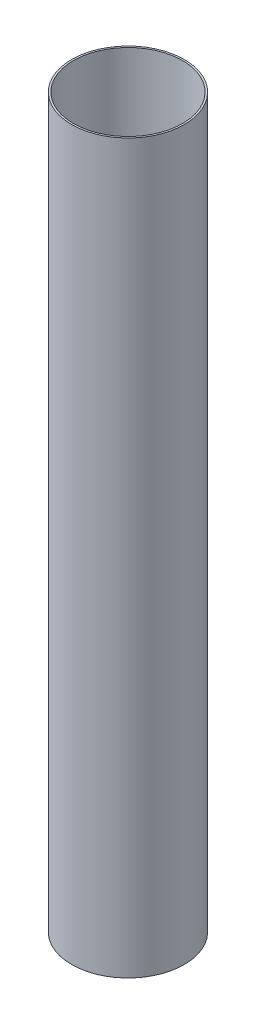
SolidWorks part; units mm, degrees
ref_plane "Front Plane" through (0, 0, 0) normal (0, 0, 1) x (1, 0, 0)
ref_plane "Top Plane" through (0, 0, 0) normal (0, 1, 0) x (1, 0, 0)
ref_plane "Right Plane" through (0, 0, 0) normal (1, 0, 0) x (0, 0, -1)
sketch "Sketch2" plane through (0, 0, 0) normal (0, 1, 0) x (1, 0, 0)
  circle A0 centre (0, 0) radius 39.35
  circle A1 centre (0, 0) radius 38.1
extrude "Boss-Extrude1" add sketch "Sketch2" along normal blind 508
